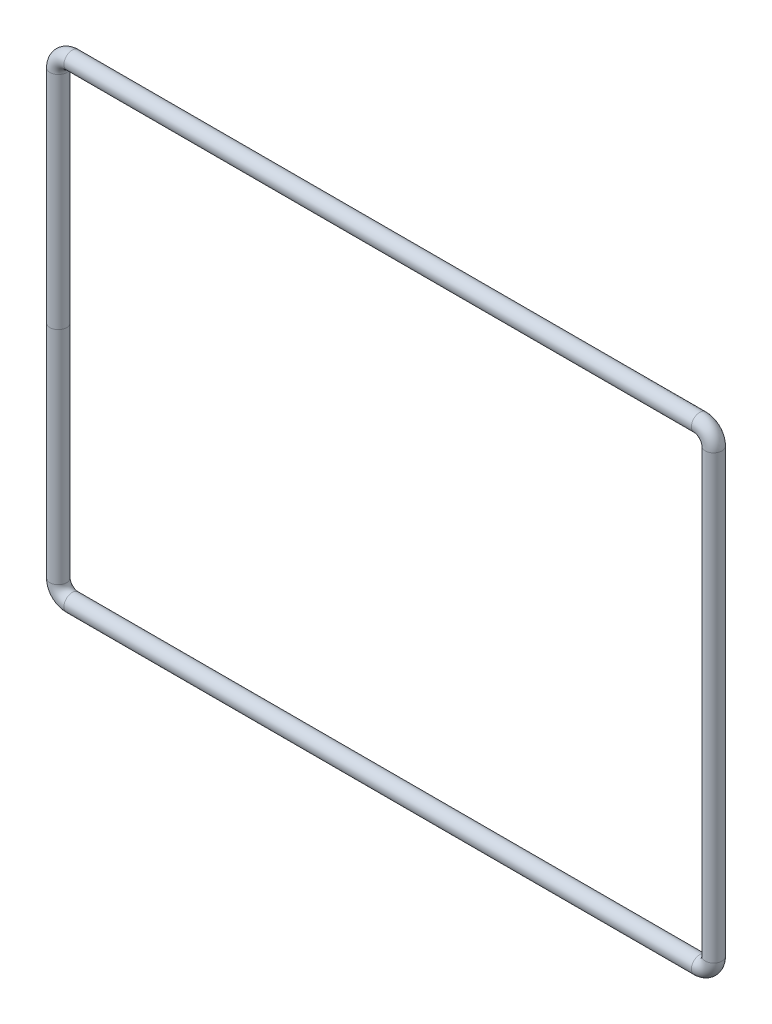
SolidWorks part; units mm, degrees
ref_plane "Спереди" through (0, 0, 0) normal (0, 0, 1) x (1, 0, 0)
ref_plane "Сверху" through (0, 0, 0) normal (0, 1, 0) x (1, 0, 0)
ref_plane "Справа" through (0, 0, 0) normal (1, 0, 0) x (0, 0, -1)
sketch "Эскиз1" plane through (0, 0, 0) normal (0, 0, 1) x (1, 0, 0)
  line L1 (-33.8, 25.3) -> (33.8, 25.3)
  line L2 (-35.3, 23.8) -> (-35.3, -23.8)
  line L3 (-33.8, -25.3) -> (33.8, -25.3)
  line L4 (35.3, 23.8) -> (35.3, -23.8)
  line L5 (-35.3, 25.3) -> (35.3, -25.3) construction
  line L6 (-35.3, -25.3) -> (35.3, 25.3) construction
  arc A1 (-35.3, 23.8) -> (-33.8, 25.3) centre (-33.8, 23.8) cw
  arc A2 (-35.3, -23.8) -> (-33.8, -25.3) centre (-33.8, -23.8) ccw
  arc A3 (33.8, -25.3) -> (35.3, -23.8) centre (33.8, -23.8) ccw
  arc A4 (35.3, 23.8) -> (33.8, 25.3) centre (33.8, 23.8) ccw
  point P0 (0, 0)
  dimension "D3" = 1.5
  dimension "D4" = 1.5
  dimension "D1" = 70.6
  dimension "D2" = 50.6
ref_plane "Плоскость4" through (0, 0, 0) normal (0, -1, 0) x (-1, 0, 0)
sketch "Эскиз2" plane through (0, 0, 0) normal (0, -1, 0) x (-1, 0, 0)
  circle A0 centre (35.3, 0) radius 0.9
  point P2 (0, 0)
  dimension "D1" = 35.3
  dimension "D2" = 1.8
  dimension "D3" = 0
sweep "По траектории1" add profiles "Эскиз2" path "Эскиз1"
